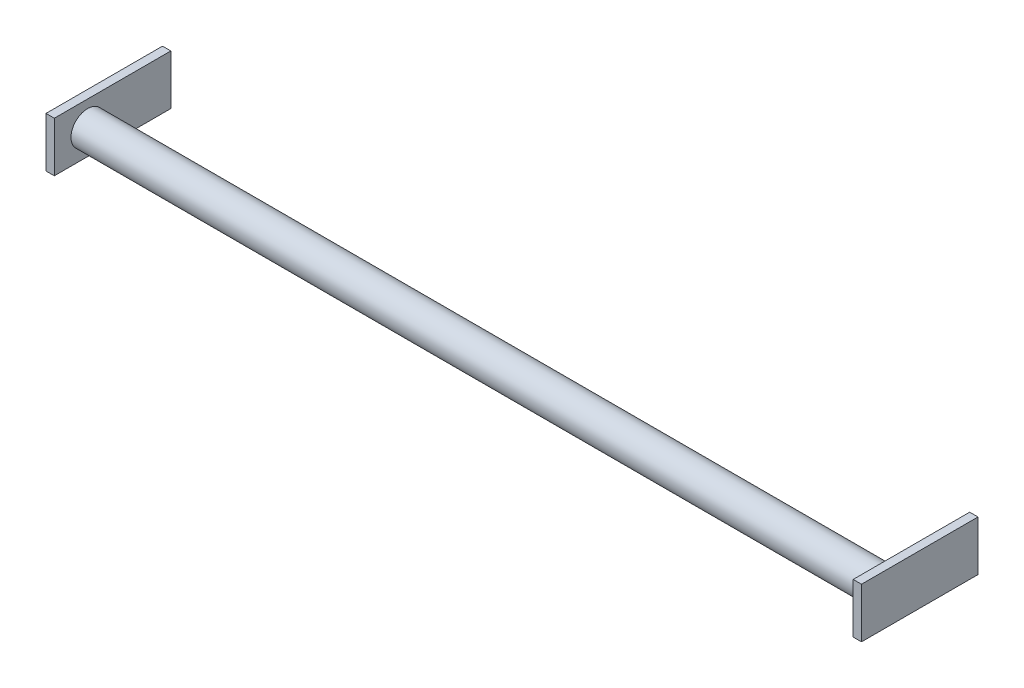
SolidWorks part; units mm, degrees
ref_plane "Front Plane" through (0, 0, 0) normal (0, 0, 1) x (1, 0, 0)
ref_plane "Top Plane" through (0, 0, 0) normal (0, 1, 0) x (1, 0, 0)
ref_plane "Right Plane" through (0, 0, 0) normal (1, 0, 0) x (0, 0, -1)
sketch "Sketch1" plane through (0, 0, 0) normal (1, 0, 0) x (0, 0, -1)
  circle A0 centre (0, 0) radius 12.7
  dimension "D1" = 25.4
extrude "Boss-Extrude1" add sketch "Sketch1" along normal mid plane 609.6
sketch "Sketch2" plane through (304.8, 0, 0) normal (1, 0, 0) x (0, 0, -1)
  line L0 (0, 55) -> (0, -55) construction
  line L1 (-25.4, 19.05) -> (63.5, 19.05)
  line L2 (-25.4, 19.05) -> (-25.4, -19.05)
  line L3 (-25.4, -19.05) -> (63.5, -19.05)
  line L4 (63.5, 19.05) -> (63.5, -19.05)
  point P4 (-25.4, 0)
  dimension "D1" = 25.4
  dimension "D2" = 38.1
  dimension "D3" = 88.9
extrude "Boss-Extrude2" add sketch "Sketch2" along normal blind 6.35
mirror "Mirror1" about plane through (0, 0, 0) normal (1, 0, 0) of "Boss-Extrude2"
